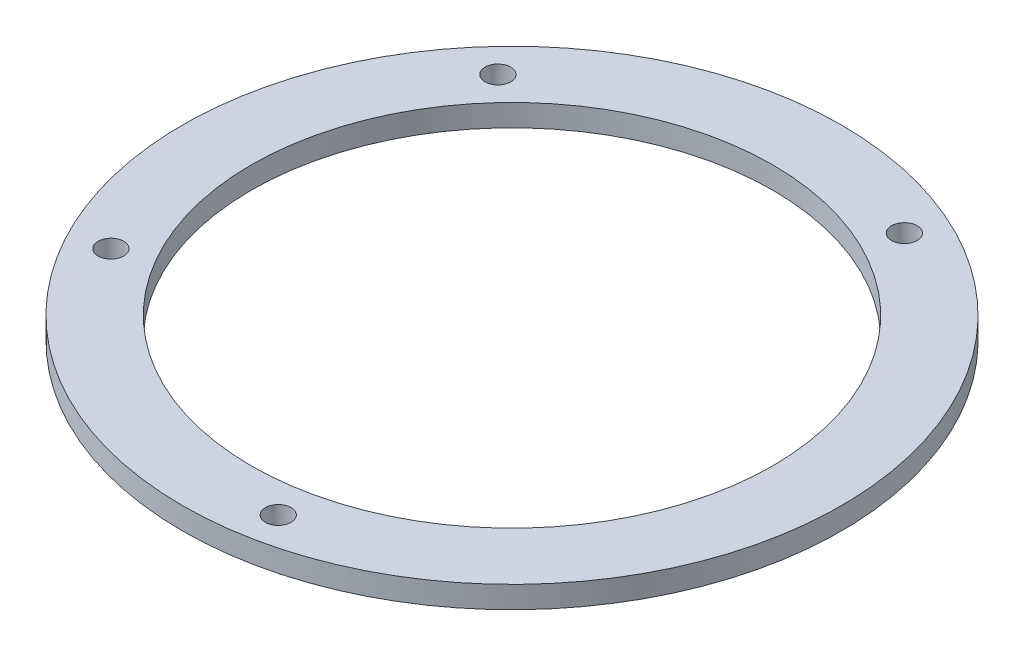
SolidWorks part; units mm, degrees
ref_plane "Front Plane" through (0, 0, 0) normal (0, 0, 1) x (1, 0, 0)
ref_plane "Top Plane" through (0, 0, 0) normal (0, 1, 0) x (1, 0, 0)
ref_plane "Right Plane" through (0, 0, 0) normal (1, 0, 0) x (0, 0, -1)
sketch "Sketch1" plane through (0, 0, 0) normal (0, 1, 0) x (1, 0, 0)
  circle A0 centre (0, 0) radius 45
  circle A1 centre (0, 0) radius 35.6
  arc A3 (10.2473, 43.8177) -> (-25.8386, 36.8425) centre (0, 0) ccw construction
  arc A4 (-19.6789, 29.6665) -> (-30.9302, 17.6263) centre (0, 0) ccw construction
  circle A5 centre (-29.4448, 27.5153) radius 1.75
  circle A6 centre (-35.2676, -19.501) radius 1.75
  circle A7 centre (7.6482, -39.5676) radius 1.75
  circle A8 centre (17.0697, 36.5064) radius 1.75
  circle A9 centre (-29.4448, 27.5153) radius 1.75 construction
extrude "Boss-Extrude1" add sketch "Sketch1" along normal blind 3
